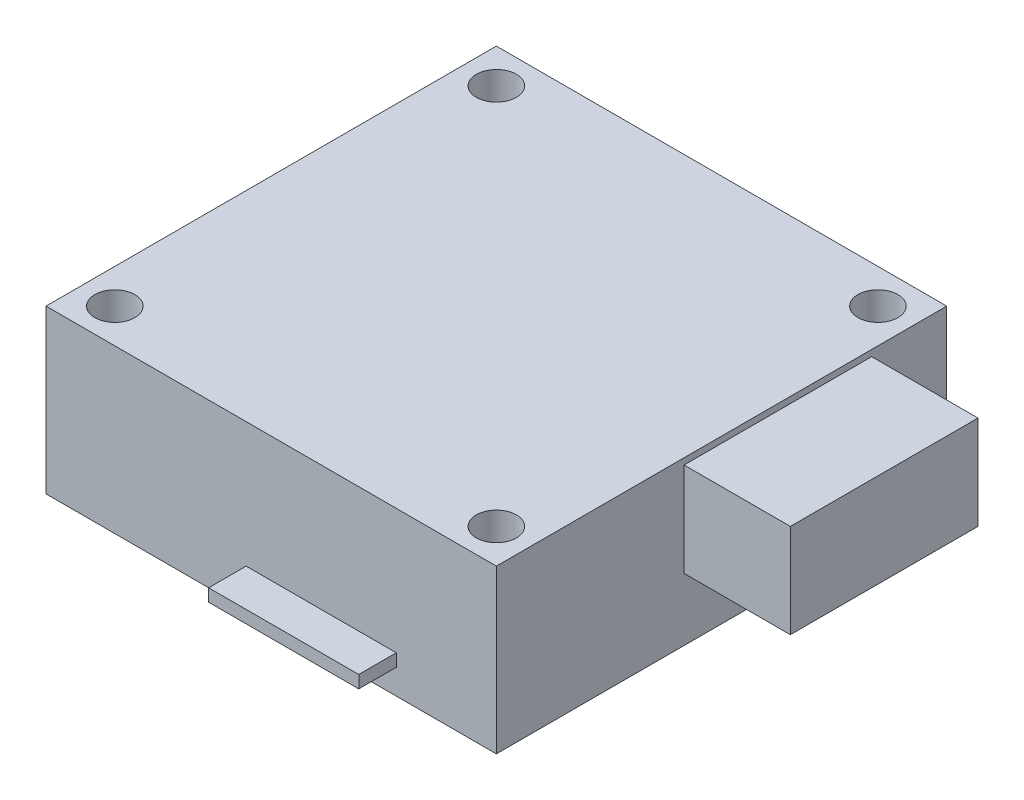
SolidWorks part; units mm, degrees
ref_plane "Ebene vorne" through (0, 0, 0) normal (0, 0, 1) x (1, 0, 0)
ref_plane "Ebene oben" through (0, 0, 0) normal (0, 1, 0) x (1, 0, 0)
ref_plane "Ebene rechts" through (0, 0, 0) normal (1, 0, 0) x (0, 0, -1)
sketch "Sketch1" plane through (0, 0, 0) normal (0, 1, 0) x (1, 0, 0)
  line L0 (0, 14.5059) -> (0, -19.8) construction
  line L1 (-13.9765, 0) -> (32.6118, 0) construction
  line L3 (-18, 18) -> (18, 18)
  line L4 (-18, 18) -> (-18, -18)
  line L5 (-18, -18) -> (18, -18)
  line L6 (18, 18) -> (18, -18)
  circle A0 centre (-15.25, 15.25) radius 1.6
  circle A1 centre (15.25, 15.25) radius 1.6
  circle A2 centre (15.25, -15.25) radius 1.6
  circle A3 centre (-15.25, -15.25) radius 1.6
  dimension "D3" = 3.2
  dimension "D1" = 36
  dimension "D2" = 36
  dimension "D4" = 30.5
  dimension "D5" = 30.5
extrude "Boss-Extrude1" add sketch "Sketch1" along normal blind 13
sketch "Sketch2" plane through (18, 0, 0) normal (1, 0, 0) x (0, 0, -1)
  line L0 (18, 13) -> (18, 0) construction
  line L1 (-3, 12.5) -> (12, 12.5)
  line L2 (-3, 12.5) -> (-3, 5)
  line L3 (-3, 5) -> (12, 5)
  line L4 (12, 12.5) -> (12, 5)
  line L5 (-18, 0) -> (18, 0) construction
  dimension "D1" = 15
  dimension "D2" = 7.5
  dimension "D3" = 6
  dimension "D4" = 5
extrude "Boss-Extrude2" add sketch "Sketch2" along normal blind 8.5
sketch "Sketch3" plane through (0, 0, 18) normal (0, 0, 1) x (1, 0, 0)
  line L0 (-18, 0) -> (18, 0) construction
  line L1 (-2, 3) -> (10, 3)
  line L2 (-2, 3) -> (-2, 2)
  line L3 (-2, 2) -> (10, 2)
  line L4 (10, 3) -> (10, 2)
  line L5 (18, 13) -> (18, 0) construction
  dimension "D1" = 12
  dimension "D2" = 1
  dimension "D3" = 2
  dimension "D4" = 8
extrude "Boss-Extrude3" add sketch "Sketch3" along normal blind 3
